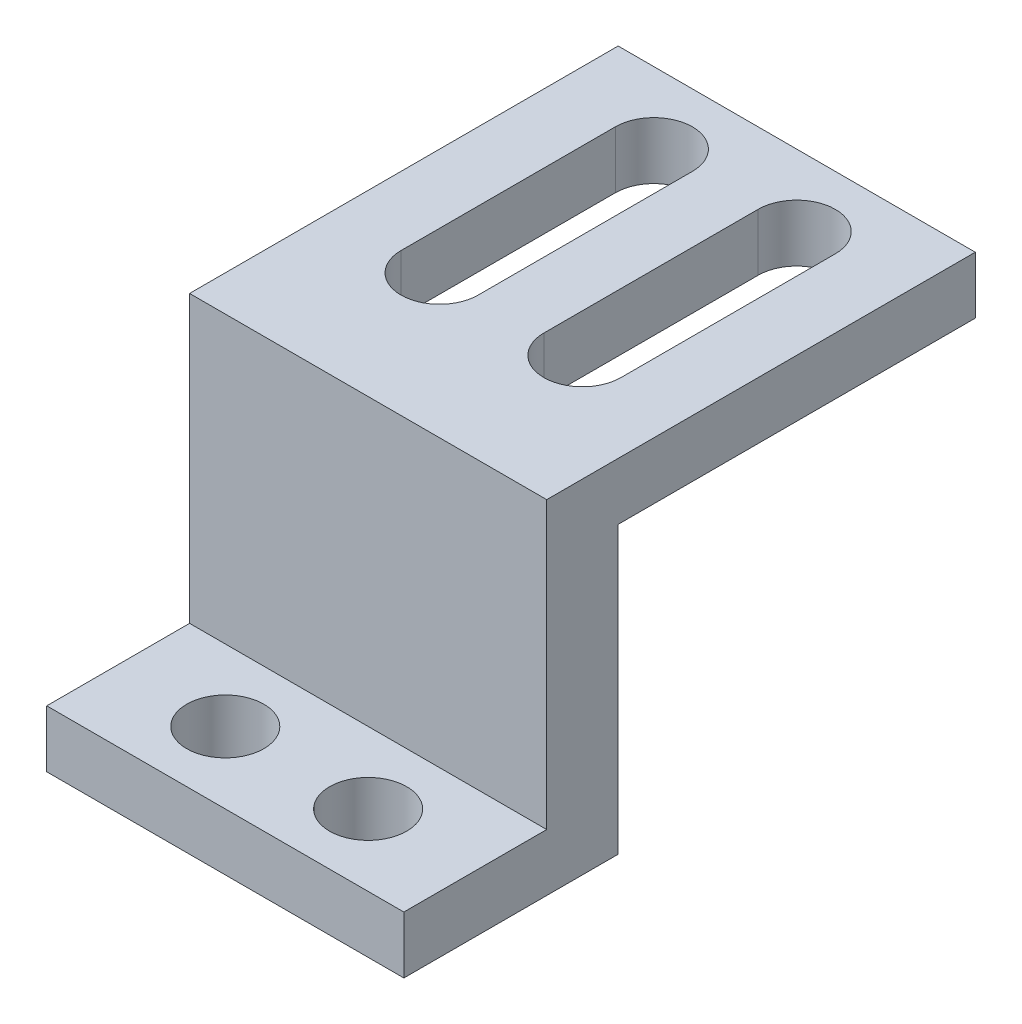
SolidWorks part; units mm, degrees
ref_plane "Front Plane" through (0, 0, 0) normal (0, 0, 1) x (1, 0, 0)
ref_plane "Top Plane" through (0, 0, 0) normal (0, 1, 0) x (1, 0, 0)
ref_plane "Right Plane" through (0, 0, 0) normal (1, 0, 0) x (0, 0, -1)
sketch "Sketch1" plane through (0, 0, 0) normal (1, 0, 0) x (0, 0, -1)
  line L0 (0, 0) -> (19.05, 0)
  line L1 (19.05, 0) -> (19.05, 25.4)
  line L2 (19.05, 25.4) -> (31.75, 25.4)
  line L4 (31.75, 30.48) -> (12.7, 30.48)
  line L5 (12.7, 30.48) -> (12.7, 5.08)
  line L6 (12.7, 5.08) -> (0, 5.08)
  line L7 (0, 5.08) -> (0, 0)
  line L8 (31.75, 30.48) -> (50.8, 30.48)
  line L9 (50.8, 30.48) -> (50.8, 25.4)
  line L10 (50.8, 25.4) -> (31.75, 25.4)
  dimension "D1" = 6.35
  dimension "D2" = 12.7
  dimension "D3" = 25.4
  dimension "D4" = 5.08
  dimension "D5" = 31.75
extrude "Boss-Extrude1" add sketch "Sketch1" along normal mid plane 31.75
sketch "Sketch2" plane through (0, 5.08, 0) normal (0, 1, 0) x (1, 0, 0)
  line L0 (15.875, 0) -> (-15.875, 0) construction
  line L1 (-15.875, 12.7) -> (-15.875, 0) construction
  line L2 (-6.35, 44.45) -> (-6.35, 25.4) construction
  line L3 (-2.921, 44.45) -> (-2.921, 25.4)
  line L4 (-9.779, 44.45) -> (-9.779, 25.4)
  line L5 (15.875, 50.8) -> (-15.875, 50.8) construction
  line L6 (6.35, 44.45) -> (6.35, 25.4) construction
  line L7 (9.779, 44.45) -> (9.779, 25.4)
  line L8 (2.921, 44.45) -> (2.921, 25.4)
  circle A0 centre (-6.35, 6.35) radius 3.429
  circle A1 centre (6.35, 6.35) radius 3.429
  arc A2 (-2.921, 44.45) -> (-9.779, 44.45) centre (-6.35, 44.45) ccw
  arc A3 (-9.779, 25.4) -> (-2.921, 25.4) centre (-6.35, 25.4) ccw
  arc A4 (9.779, 44.45) -> (2.921, 44.45) centre (6.35, 44.45) ccw
  arc A5 (2.921, 25.4) -> (9.779, 25.4) centre (6.35, 25.4) ccw
  point P10 (-6.35, 34.925)
  point P21 (6.35, 34.925)
  dimension "D2" = 6.858
  dimension "D6" = 19.05
  dimension "D1" = 6.35
  dimension "D3" = 9.525
  dimension "D5" = 6.858
  dimension "D7" = 6.35
  dimension "D4" = 2
  dimension "D8" = 2
extrude "Cut-Extrude1" cut sketch "Sketch2" against normal through all both and the other way through all
